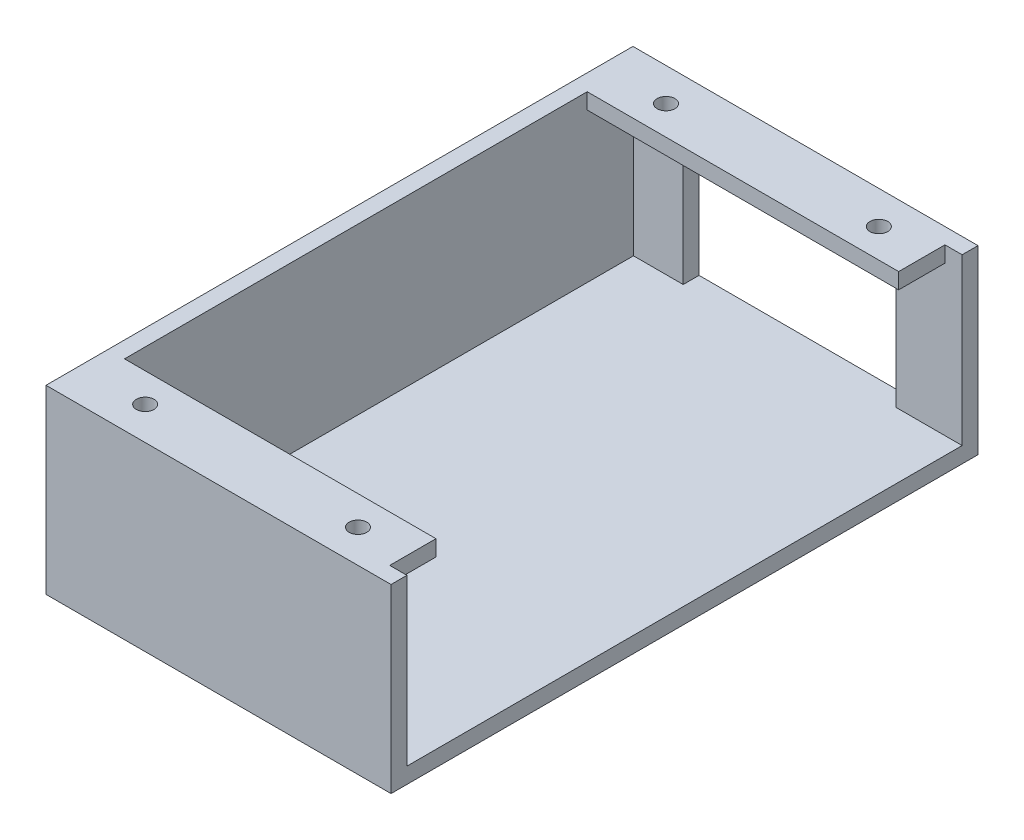
SolidWorks part; units mm, degrees
material "ABS"
ref_plane "Front Plane" through (0, 0, 0) normal (0, 0, 1) x (1, 0, 0)
ref_plane "Top Plane" through (0, 0, 0) normal (0, 1, 0) x (1, 0, 0)
ref_plane "Right Plane" through (0, 0, 0) normal (1, 0, 0) x (0, 0, -1)
sketch "Sketch1" plane through (0, 0, 0) normal (0, 1, 0) x (1, 0, 0)
  line L0 (-33.147, 56.388) -> (33.147, 56.388)
  line L1 (-30.099, 53.34) -> (30.099, 53.34)
  line L2 (-30.099, 53.34) -> (-30.099, -53.34)
  line L3 (-30.099, -53.34) -> (30.099, -53.34)
  line L4 (30.099, 53.34) -> (30.099, -53.34)
  line L5 (-30.099, 53.34) -> (30.099, -53.34) construction
  line L6 (-30.099, -53.34) -> (30.099, 53.34) construction
  line L7 (33.147, 56.388) -> (33.147, -56.388)
  line L8 (-33.147, -56.388) -> (33.147, -56.388)
  line L9 (-33.147, 56.388) -> (-33.147, -56.388)
  point P0 (0, 0)
  dimension "D1" = 60.198
  dimension "D2" = 106.68
  dimension "D3" = 3.048
extrude "Boss-Extrude1" add sketch "Sketch1" along normal blind 3.048 contours L9 L8 L7 L0
sketch "Sketch2" plane through (0, 3.048, 0) normal (0, 1, 0) x (1, 0, 0)
  line L1 (-33.147, 56.388) -> (33.147, 56.388)
  line L2 (-33.147, 56.388) -> (-33.147, -56.388)
  line L3 (-33.147, -56.388) -> (33.147, -56.388)
  line L4 (33.147, 56.388) -> (33.147, -56.388)
  line L5 (-33.147, 56.388) -> (33.147, -56.388) construction
  line L6 (-33.147, -56.388) -> (33.147, 56.388) construction
  line L7 (-30, 53.34) -> (30, 53.34)
  line L8 (-30, 53.34) -> (-30, -53.34)
  line L9 (-30, -53.34) -> (30, -53.34)
  line L10 (30, 53.34) -> (30, -53.34)
  line L11 (-30, 53.34) -> (30, -53.34) construction
  line L12 (-30, -53.34) -> (30, 53.34) construction
  point P0 (0, 0)
  point P7 (0, 0)
  dimension "D1" = 106.68
  dimension "D2" = 60
extrude "Boss-Extrude2" add sketch "Sketch2" along normal blind 31.75
sketch "Sketch3" plane through (0, 34.798, 0) normal (0, 1, 0) x (1, 0, 0)
  line L1 (-30, 53.34) -> (30, 53.34)
  line L2 (-30, 53.34) -> (-30, 44.45)
  line L3 (-30, 44.45) -> (30, 44.45)
  line L4 (30, 53.34) -> (30, 44.45)
  line L5 (-30, -53.34) -> (30, -53.34)
  line L6 (-30, -53.34) -> (-30, -44.45)
  line L7 (-30, -44.45) -> (30, -44.45)
  line L8 (30, -53.34) -> (30, -44.45)
  point P20 (-23.65, 47.625)
  point P21 (-23.65, -50.165)
  dimension "D2" = 8.89
  dimension "D3" = 8.89
  dimension "D9" = 6.35
  dimension "D10" = 3.175
  dimension "D11" = 6.35
  dimension "D12" = 3.175
extrude "Boss-Extrude3" add sketch "Sketch3" against normal blind 3.048
sketch "Sketch6" plane through (33.147, 0, 0) normal (1, 0, 0) x (0, 0, -1)
  line L0 (53.34, 31.75) -> (53.34, 3.048) construction
  line L1 (-53.34, 3.048) -> (53.34, 3.048)
  line L2 (-53.34, 3.048) -> (-53.34, 34.798)
  line L3 (-53.34, 34.798) -> (53.34, 34.798)
  line L4 (53.34, 3.048) -> (53.34, 34.798)
  line L5 (-56.388, 34.798) -> (56.388, 34.798) construction
  line L6 (56.388, 0) -> (-56.388, 0) construction
  line L9 (-53.34, 31.75) -> (-53.34, 3.048) construction
  point P6 (0, 3.048)
  dimension "D2" = 3.048
extrude "Cut-Extrude1" cut sketch "Sketch6" against normal blind 3.302
sketch "Sketch10" plane through (0, 34.798, 0) normal (0, 1, 0) x (1, 0, 0)
  line L0 (-33.147, 56.388) -> (-33.147, -56.388) construction
  line L1 (33.147, 56.388) -> (-33.147, 56.388) construction
  line L2 (33.147, -53.34) -> (33.147, 53.34) construction
  line L3 (-33.147, -56.388) -> (33.147, -56.388) construction
  circle A0 centre (-20.447, 50.038) radius 2.75
  circle A1 centre (20.447, 50.038) radius 2.75
  circle A2 centre (-20.447, -50.038) radius 2.75
  circle A3 centre (20.447, -50.038) radius 2.75
  point P17 (-20.447, 50.038)
  point P18 (20.447, 50.038)
  point P19 (-20.447, -50.038)
  point P20 (20.447, -50.038)
  dimension "D1" = 5.5
  dimension "D2" = 5.5
  dimension "D3" = 5.5
  dimension "D4" = 5.5
  dimension "D5" = 12.7
  dimension "D6" = 6.35
  dimension "D7" = 6.35
  dimension "D8" = 12.7
  dimension "D9" = 12.7
  dimension "D10" = 12.7
  dimension "D11" = 6.35
  dimension "D12" = 6.35
hole_wizard "M3 Clearance Hole1" positions "3DSketch1" profile "Sketch11" hole size "M3" standard "ISO"
sketch3d "3DSketch1"
  point P0 (-20.447, 34.798, -50.038)
  point P3 (20.447, 34.798, -50.038)
  point P6 (-20.447, 34.798, 50.038)
  point P9 (20.447, 34.798, 50.038)
sketch "Sketch11" plane through (-20.447, 34.798, -50.038) normal (1, 0, 0) x (0, 0, 1)
  line L0 (0, 0) -> (0, 3.048)
  line L1 (0, 3.048) -> (1.7, 3.048)
  line L2 (1.7, 3.048) -> (1.7, 0)
  line L5 (1.7, 0) -> (0, 0)
  line L11 (0, -6.35) -> (0, 107.95) construction
  dimension "Thru Hole Dia." = 3.4
  dimension "Thru Hole Depth" = 3.048
sketch "Sketch12" plane through (0, 0, -56.388) normal (0, 0, -1) x (-1, 0, 0)
  line L0 (-33.147, 34.798) -> (-33.147, 0) construction
  line L1 (-20.447, 3.048) -> (20.447, 3.048)
  line L2 (-20.447, 3.048) -> (-20.447, 23.368)
  line L3 (-20.447, 23.368) -> (20.447, 23.368)
  line L4 (20.447, 3.048) -> (20.447, 23.368)
  line L5 (33.147, 34.798) -> (33.147, 0) construction
  line L6 (33.147, 0) -> (-33.147, 0) construction
  dimension "D1" = 12.7
  dimension "D2" = 12.7
  dimension "D3" = 3.048
  dimension "D4" = 20.32
extrude "Cut-Extrude4" cut sketch "Sketch12" against normal up to next
sketch "Sketch13" plane through (0, 0, 0) normal (0, -1, 0) x (1, 0, 0)
  line L1 (-8.89, 10.16) -> (8.89, 10.16)
  line L2 (-8.89, 10.16) -> (-8.89, -10.16)
  line L3 (-8.89, -10.16) -> (8.89, -10.16)
  line L4 (8.89, 10.16) -> (8.89, -10.16)
  line L5 (-8.89, 10.16) -> (8.89, -10.16) construction
  line L6 (-8.89, -10.16) -> (8.89, 10.16) construction
  line L7 (-8.89, 10.16) -> (8.89, 10.16)
  line L8 (-8.89, 10.16) -> (-8.89, 15.24)
  line L9 (-8.89, 15.24) -> (8.89, 15.24)
  line L10 (8.89, 10.16) -> (8.89, 15.24)
  line L11 (-8.89, -10.16) -> (8.89, -10.16)
  line L12 (-8.89, -10.16) -> (-8.89, -15.24)
  line L13 (-8.89, -15.24) -> (8.89, -15.24)
  line L14 (8.89, -10.16) -> (8.89, -15.24)
  point P0 (0, 0)
  dimension "D1" = 10.16
  dimension "D2" = 17.78
  dimension "D3" = 5.08
  dimension "D4" = 5.08
extrude "Boss-Extrude4" add sketch "Sketch13" along normal blind 5.08 contours L1 L10 L9 L8 | L14 L3 L12 L13
sketch "Sketch14" plane through (0, 0, 10.16) normal (0, 0, -1) x (-1, 0, 0)
  line L1 (-8.89, -5.08) -> (8.89, -5.08)
  line L2 (-8.89, -5.08) -> (-8.89, -2.54)
  line L3 (-8.89, -2.54) -> (8.89, -2.54)
  line L4 (8.89, -5.08) -> (8.89, -2.54)
  line L5 (8.89, -5.08) -> (-8.89, -5.08) construction
  line L6 (8.89, -5.08) -> (8.89, 0) construction
  line L7 (-8.89, -5.08) -> (-8.89, 0) construction
  dimension "D1" = 2.54
ref_plane "Plane1" through (0, 0, 0) normal (0, 0, -1) x (-1, 0, 0)
extrude "Boss-Extrude6" add sketch "Sketch14" along normal blind 5.08
mirror "Mirror2" about plane through (0, 0, 0) normal (0, 0, -1) of "Boss-Extrude6"
